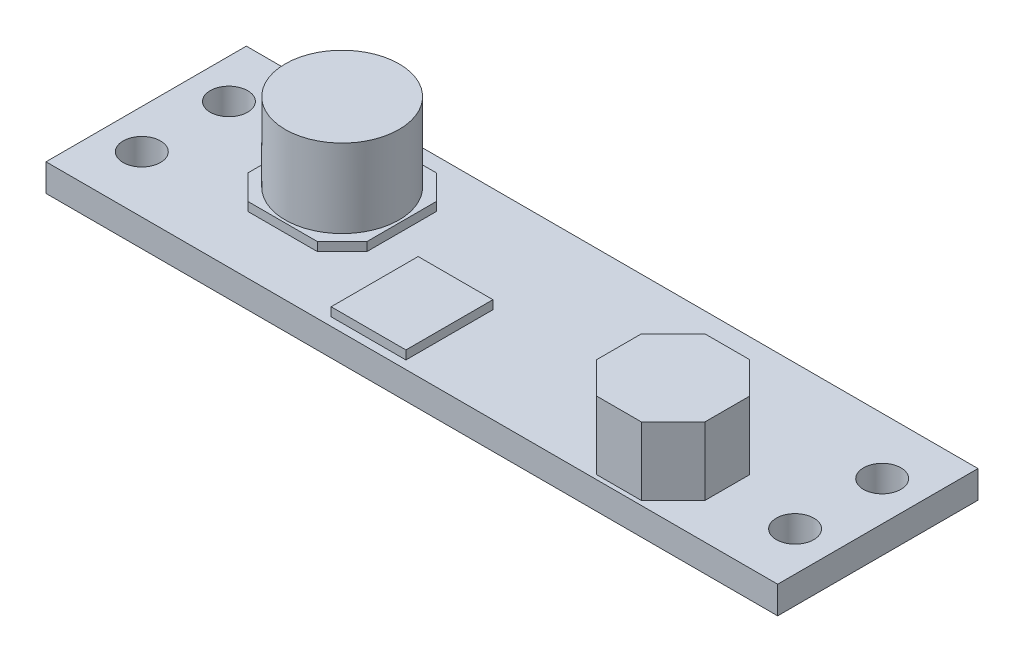
SolidWorks part; units mm, degrees
ref_plane "Front Plane" through (0, 0, 0) normal (0, 0, 1) x (1, 0, 0)
ref_plane "Top Plane" through (0, 0, 0) normal (0, 1, 0) x (1, 0, 0)
ref_plane "Right Plane" through (0, 0, 0) normal (1, 0, 0) x (0, 0, -1)
sketch "Sketch1" plane through (0, 0, 0) normal (0, 1, 0) x (1, 0, 0)
  line L0 (-19.05, 2.54) -> (19.05, 2.54) construction
  line L1 (-21.336, -5.842) -> (21.336, -5.842)
  line L2 (-21.336, -5.842) -> (-21.336, 5.842)
  line L3 (-21.336, 5.842) -> (21.336, 5.842)
  line L4 (21.336, -5.842) -> (21.336, 5.842)
  line L5 (-21.336, -5.842) -> (21.336, 5.842) construction
  line L6 (-21.336, 5.842) -> (21.336, -5.842) construction
  line L7 (0, 0) -> (0, 2.54) construction
  line L8 (-19.05, 2.54) -> (-19.05, 1.4478) construction
  line L9 (19.05, 2.54) -> (19.05, -2.54) construction
  line L10 (0, 0) -> (19.05, 0) construction
  line L11 (19.05, -2.54) -> (17.9578, -2.54) construction
  circle A0 centre (-19.05, 2.54) radius 1.0922
  circle A1 centre (-19.05, -2.54) radius 1.0922
  circle A2 centre (19.05, 2.54) radius 1.0922
  circle A3 centre (19.05, -2.54) radius 1.0922
  point P0 (0, 0)
  dimension "D4" = 2.1844
  dimension "D5" = 2.1844
  dimension "D6" = 2.1844
  dimension "D7" = 5.08
  dimension "D8" = 2.1844
  dimension "D1" = 42.672
  dimension "D2" = 11.684
  dimension "D3" = 38.1
extrude "Boss-Extrude1" add sketch "Sketch1" along normal blind 1.6002
sketch "Sketch2" plane through (0, 1.6002, 0) normal (0, 1, 0) x (1, 0, 0)
  line L1 (-0.8299, -5.3574) -> (-5.1907, -5.3574)
  line L2 (-0.8299, -5.3574) -> (-0.8299, -0.2831)
  line L3 (-0.8299, -0.2831) -> (-5.1907, -0.2831)
  line L4 (-5.1907, -5.3574) -> (-5.1907, -0.2831)
extrude "Boss-Extrude2" add sketch "Sketch2" along normal blind 0.508
sketch "Sketch3" plane through (0, 1.6002, 0) normal (0, 1, 0) x (1, 0, 0)
  line L0 (-7.4409, -1.0288) -> (-7.4409, 3.0352)
  line L1 (-7.4409, 3.0352) -> (-8.8778, 4.4721)
  line L2 (-7.4409, -1.0288) -> (-8.8778, -2.4656)
  line L3 (-8.8778, -2.4656) -> (-12.9418, -2.4656)
  line L4 (-12.9418, -2.4656) -> (-14.3786, -1.0288)
  line L5 (-14.3786, -1.0288) -> (-14.3786, 3.0352)
  line L6 (-14.3786, 3.0352) -> (-12.9418, 4.4721)
  line L7 (-12.9418, 4.4721) -> (-8.8778, 4.4721)
  dimension "D1" = 2.032
  dimension "D2" = 2.032
  dimension "D3" = 135
  dimension "D4" = 135
  dimension "D5" = 4.064
  dimension "D6" = 4.064
extrude "Boss-Extrude3" add sketch "Sketch3" along normal blind 0.508
sketch "Sketch4" plane through (0, 2.1082, 0) normal (0, 1, 0) x (1, 0, 0)
  line L0 (-12.9418, -2.4656) -> (-8.8778, -2.4656) construction
  line L1 (-7.4409, -1.0288) -> (-7.4409, 3.0352) construction
  line L2 (-7.4409, 1.0032) -> (-10.9098, 1.0032) construction
  line L3 (-10.9098, 1.0032) -> (-10.9098, -2.4656) construction
  circle A0 centre (-10.9098, 1.0032) radius 3.3183
extrude "Boss-Extrude4" add sketch "Sketch4" along normal blind 4.572
sketch "Sketch5" plane through (0, 1.6002, 0) normal (0, 1, 0) x (1, 0, 0)
  line L1 (14.986, -3.7419) -> (14.986, -1.1318)
  line L2 (14.986, -1.1318) -> (13.1404, 0.7139)
  line L3 (13.1404, 0.7139) -> (10.5302, 0.7139)
  line L4 (10.5302, 0.7139) -> (8.6846, -1.1318)
  line L5 (8.6846, -1.1318) -> (8.6846, -3.7419)
  line L6 (8.6846, -3.7419) -> (10.5302, -5.5875)
  line L7 (10.5302, -5.5875) -> (13.1404, -5.5875)
  line L8 (13.1404, -5.5875) -> (14.986, -3.7419)
  line L9 (21.336, -5.842) -> (21.336, 5.842) construction
  circle A0 centre (11.8353, -2.4368) radius 3.1507 construction
  dimension "D1" = 6.35
extrude "Boss-Extrude5" add sketch "Sketch5" along normal blind 3.9688
